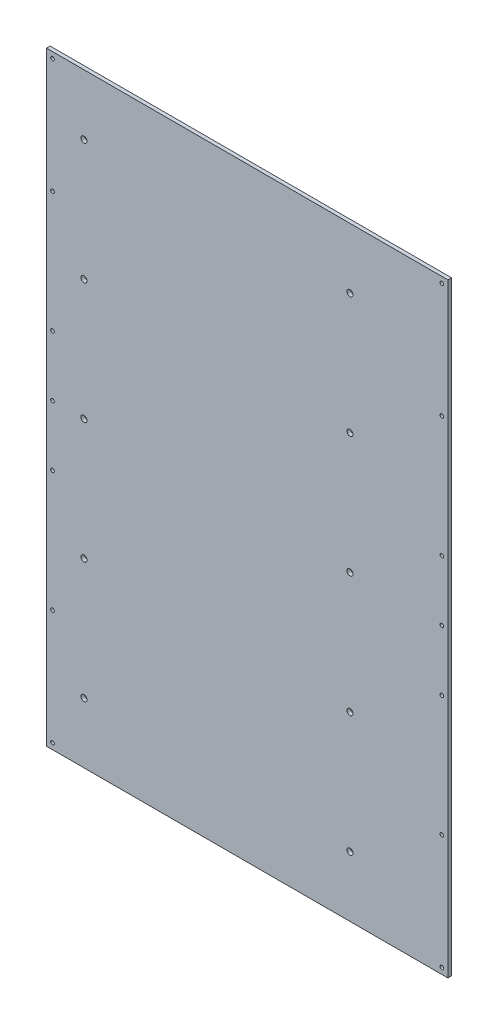
SolidWorks part; units mm, degrees
ref_plane "前视基准面" through (0, 0, 0) normal (0, 0, 1) x (1, 0, 0)
ref_plane "上视基准面" through (0, 0, 0) normal (0, 1, 0) x (1, 0, 0)
ref_plane "右视基准面" through (0, 0, 0) normal (1, 0, 0) x (0, 0, -1)
sketch "草图1" plane through (0, 0, 0) normal (0, 0, 1) x (1, 0, 0)
  line L0 (327, 537.5875) -> (327, -65.4008) construction
  line L1 (0, 0) -> (332, 0)
  line L2 (0, 0) -> (0, 500)
  line L3 (0, 500) -> (332, 500)
  line L4 (332, 0) -> (332, 500)
  line L5 (332, 250) -> (-343.4407, 250) construction
  line L6 (166, 500) -> (166, 184.5786) construction
  line L7 (251, 500) -> (251, 73.0051) construction
  line L8 (31, 500) -> (31, 450) construction
  circle A0 centre (327, 250) radius 1.5
  circle A1 centre (327, 300) radius 1.5
  circle A3 centre (327, 400) radius 1.5
  circle A5 centre (327, 495) radius 1.5
  circle A6 centre (327, 5) radius 1.5
  circle A7 centre (327, 100) radius 1.5
  circle A8 centre (327, 200) radius 1.5
  circle A9 centre (5, 200) radius 1.5
  circle A10 centre (5, 100) radius 1.5
  circle A11 centre (5, 5) radius 1.5
  circle A12 centre (5, 495) radius 1.5
  circle A13 centre (5, 400) radius 1.5
  circle A14 centre (5, 300) radius 1.5
  circle A15 centre (5, 250) radius 1.5
  circle A16 centre (251, 250) radius 2.5
  circle A17 centre (251, 150) radius 2.5
  circle A18 centre (251, 50) radius 2.5
  circle A19 centre (251, 350) radius 2.5
  circle A20 centre (251, 450) radius 2.5
  circle A21 centre (31, 150) radius 2.5
  circle A22 centre (31, 350) radius 2.5
  circle A23 centre (31, 450) radius 2.5
  circle A24 centre (31, 250) radius 2.5
  circle A25 centre (31, 50) radius 2.5
  dimension "D4" = 100
  dimension "D8" = 5
  dimension "D9" = 100
  dimension "D1" = 500
  dimension "D2" = 332
  dimension "D3" = 5
  dimension "D5" = 100
  dimension "D6" = 166
  dimension "D7" = 251
  dimension "D10" = 200
  dimension "D11" = 100
  dimension "D12" = 200
  dimension "D13" = 31
  dimension "D14" = 100
  dimension "D15" = 200
  dimension "D16" = 100
  dimension "D17" = 200
extrude "凸台-拉伸1" add sketch "草图1" along normal blind 3
